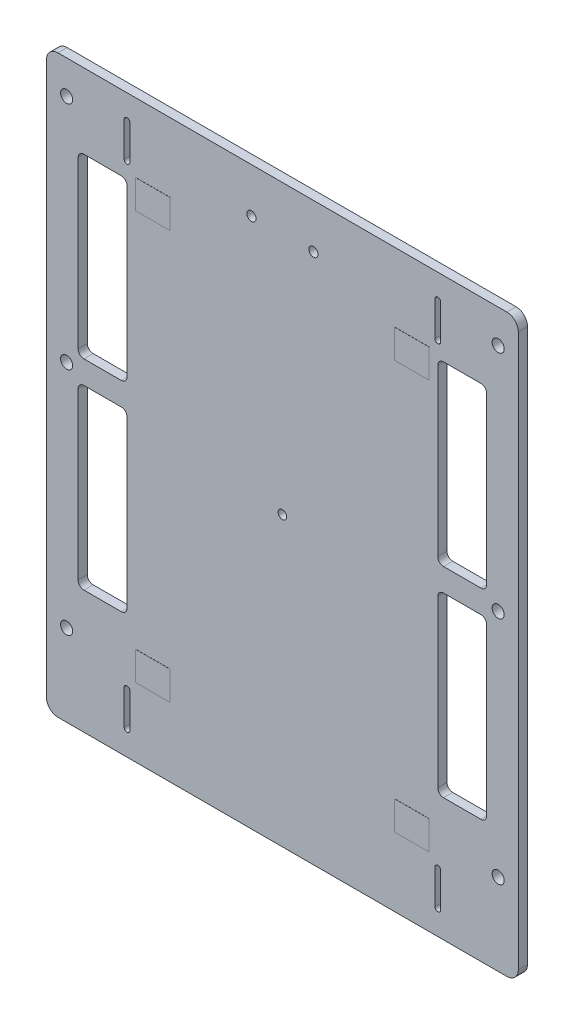
SolidWorks part; units mm, degrees
ref_plane "Front Plane" through (0, 0, 0) normal (0, 0, 1) x (1, 0, 0)
ref_plane "Top Plane" through (0, 0, 0) normal (0, 1, 0) x (1, 0, 0)
ref_plane "Right Plane" through (0, 0, 0) normal (1, 0, 0) x (0, 0, -1)
sketch "Sketch1" plane through (0, 0, 0) normal (0, 0, 1) x (1, 0, 0)
  line L1 (-39, -50) -> (39, -50)
  line L2 (-41, -48) -> (-41, 48)
  line L3 (-39, 50) -> (39, 50)
  line L4 (41, -48) -> (41, 48)
  line L5 (-41, -50) -> (41, 50) construction
  line L6 (-41, 50) -> (41, -50) construction
  arc A0 (-39, -50) -> (-41, -48) centre (-39, -48) cw
  arc A1 (39, -50) -> (41, -48) centre (39, -48) ccw
  arc A2 (39, 50) -> (41, 48) centre (39, 48) cw
  arc A3 (-41, 48) -> (-39, 50) centre (-39, 48) cw
  point P0 (0, 0)
  dimension "D3" = 2
  dimension "D1" = 100
  dimension "D2" = 82
extrude "Boss-Extrude1" add sketch "Sketch1" along normal blind 1.6
sketch "Sketch2" plane through (0, 0, 1.6) normal (0, 0, 1) x (1, 0, 0)
  line L0 (39, 50) -> (-39, 50) construction
  line L1 (-41, 48) -> (-41, -48) construction
  line L3 (-37.5, 44.2) -> (-37.5, 4.2) construction
  circle A0 centre (0, 0) radius 0.75
  circle A1 centre (-37.5, 44.2) radius 1.05
  circle A2 centre (37.5, 44.2) radius 1.05
  circle A3 centre (37.5, 4.2) radius 1.05
  circle A4 centre (37.5, -35.8) radius 1.05
  circle A5 centre (-37.5, 4.2) radius 1.05
  circle A6 centre (-37.5, -35.8) radius 1.05
  circle A7 centre (-5.38, 42.25) radius 0.8
  circle A8 centre (5.39, 42.25) radius 0.8
  dimension "D1" = 1.5
  dimension "D2" = 2.1
  dimension "D9" = 10.77
  dimension "D7" = 1.6
  dimension "D11" = 7.75
  dimension "D12" = 35.62
  dimension "D3" = 5.8
  dimension "D4" = 3.5
  dimension "D8" = 40
  dimension "D10" = 37.5
  dimension "D5" = 2
  dimension "D6" = 3
extrude "Cut-Extrude1" cut sketch "Sketch2" against normal through all
sketch "Sketch3" plane through (0, 0, 1.6) normal (0, 0, 1) x (1, 0, 0)
  line L0 (39, 50) -> (-39, 50) construction
  line L1 (-34.5, 37) -> (-28, 37)
  line L2 (-35.5, 36) -> (-35.5, 7.2)
  line L3 (-34.5, 6.2) -> (-28, 6.2)
  line L4 (-27, 36) -> (-27, 7.2)
  line L5 (-41, 48) -> (-41, -48) construction
  line L6 (28, 37) -> (34.5, 37)
  line L7 (27, 36) -> (27, 7.2)
  line L8 (35.5, 36) -> (35.5, 7.2)
  line L9 (28, 6.2) -> (34.5, 6.2)
  line L10 (28, 2.2) -> (34.5, 2.2)
  line L11 (27, 1.2) -> (27, -27.6)
  line L12 (35.5, 1.2) -> (35.5, -27.6)
  line L13 (28, -28.6) -> (34.5, -28.6)
  line L14 (-34.5, 2.2) -> (-28, 2.2)
  line L15 (-35.5, 1.2) -> (-35.5, -27.6)
  line L16 (-27, 1.2) -> (-27, -27.6)
  line L17 (-34.5, -28.6) -> (-28, -28.6)
  line L18 (-34.5, 37) -> (28, 37) construction
  line L19 (-39, -50) -> (39, -50) construction
  arc A0 (-35.5, 7.2) -> (-34.5, 6.2) centre (-34.5, 7.2) ccw
  arc A1 (-28, 6.2) -> (-27, 7.2) centre (-28, 7.2) ccw
  arc A2 (-28, 37) -> (-27, 36) centre (-28, 36) cw
  arc A3 (-34.5, 37) -> (-35.5, 36) centre (-34.5, 36) ccw
  arc A4 (28, 37) -> (27, 36) centre (28, 36) ccw
  arc A5 (34.5, 37) -> (35.5, 36) centre (34.5, 36) cw
  arc A6 (27, 7.2) -> (28, 6.2) centre (28, 7.2) ccw
  arc A7 (34.5, 6.2) -> (35.5, 7.2) centre (34.5, 7.2) ccw
  arc A8 (28, 2.2) -> (27, 1.2) centre (28, 1.2) ccw
  arc A9 (34.5, 2.2) -> (35.5, 1.2) centre (34.5, 1.2) cw
  arc A10 (27, -27.6) -> (28, -28.6) centre (28, -27.6) ccw
  arc A11 (34.5, -28.6) -> (35.5, -27.6) centre (34.5, -27.6) ccw
  arc A12 (-34.5, 2.2) -> (-35.5, 1.2) centre (-34.5, 1.2) ccw
  arc A13 (-28, 2.2) -> (-27, 1.2) centre (-28, 1.2) cw
  arc A14 (-35.5, -27.6) -> (-34.5, -28.6) centre (-34.5, -27.6) ccw
  arc A15 (-28, -28.6) -> (-27, -27.6) centre (-28, -27.6) ccw
  point P12 (-27, 6.2)
  point P15 (-27, 37)
  point P18 (-35.5, 37)
  dimension "D5" = 1
  dimension "D10" = 27
  dimension "D1" = 8.5
  dimension "D2" = 30.8
  dimension "D3" = 13
  dimension "D4" = 5.5
  dimension "D8" = 62.5
  dimension "D9" = 4
  dimension "D11" = 21.4
  dimension "D6" = 2
  dimension "D7" = 2
extrude "Cut-Extrude2" cut sketch "Sketch3" against normal through all
sketch "Sketch4" plane through (0, 0, 1.6) normal (0, 0, 1) x (1, 0, 0)
  line L0 (-27, 39.75) -> (-27, 45.75) construction
  line L1 (-27.5, 39.75) -> (-27.5, 45.75)
  line L2 (-26.5, 39.75) -> (-26.5, 45.75)
  line L3 (39, 50) -> (-39, 50) construction
  line L4 (-41, 48) -> (-41, -48) construction
  line L5 (27, 39.75) -> (27, 45.75) construction
  line L6 (26.5, 39.75) -> (26.5, 45.75)
  line L7 (27.5, 39.75) -> (27.5, 45.75)
  line L8 (27, -45.75) -> (27, -39.75) construction
  line L9 (26.5, -45.75) -> (26.5, -39.75)
  line L10 (27.5, -45.75) -> (27.5, -39.75)
  line L11 (-27, -45.75) -> (-27, -39.75) construction
  line L12 (-27.5, -45.75) -> (-27.5, -39.75)
  line L13 (-26.5, -45.75) -> (-26.5, -39.75)
  line L14 (-27, 39.75) -> (27, 39.75) construction
  line L15 (-39, -50) -> (39, -50) construction
  arc A0 (-27.5, 39.75) -> (-26.5, 39.75) centre (-27, 39.75) ccw
  arc A1 (-26.5, 45.75) -> (-27.5, 45.75) centre (-27, 45.75) ccw
  arc A2 (26.5, 39.75) -> (27.5, 39.75) centre (27, 39.75) ccw
  arc A3 (27.5, 45.75) -> (26.5, 45.75) centre (27, 45.75) ccw
  arc A4 (26.5, -45.75) -> (27.5, -45.75) centre (27, -45.75) ccw
  arc A5 (27.5, -39.75) -> (26.5, -39.75) centre (27, -39.75) ccw
  arc A6 (-27.5, -45.75) -> (-26.5, -45.75) centre (-27, -45.75) ccw
  arc A7 (-26.5, -39.75) -> (-27.5, -39.75) centre (-27, -39.75) ccw
  point P2 (-27, 42.75)
  point P16 (27, 42.75)
  point P23 (27, -42.75)
  point P30 (-27, -42.75)
  dimension "D1" = 4.25
  dimension "D2" = 13.5
  dimension "D3" = 1
  dimension "D4" = 6
  dimension "D7" = 54
  dimension "D8" = 14
  dimension "D9" = 4.25
  dimension "D10" = 4.25
  dimension "D5" = 2
  dimension "D6" = 2
extrude "Cut-Extrude3" cut sketch "Sketch4" against normal blind 1.6
sketch "Sketch5" plane through (0, 0, 1.6) normal (0, 0, 1) x (1, 0, 0)
  line L0 (-41, 48) -> (-41, -48) construction
  line L1 (-25.5, 38) -> (-19.5, 38)
  line L2 (-25.5, 38) -> (-25.5, 33)
  line L3 (-25.5, 33) -> (-19.5, 33)
  line L4 (-19.5, 38) -> (-19.5, 33)
  line L5 (39, 50) -> (-39, 50) construction
  line L6 (19.5, 38) -> (19.5, 33)
  line L7 (25.5, 38) -> (25.5, 33)
  line L8 (19.5, 33) -> (25.5, 33)
  line L9 (19.5, 38) -> (25.5, 38)
  line L10 (19.5, -33) -> (19.5, -38)
  line L11 (25.5, -33) -> (25.5, -38)
  line L12 (19.5, -38) -> (25.5, -38)
  line L13 (19.5, -33) -> (25.5, -33)
  line L14 (-25.5, -33) -> (-25.5, -38)
  line L15 (-19.5, -33) -> (-19.5, -38)
  line L16 (-25.5, -38) -> (-19.5, -38)
  line L17 (-25.5, -33) -> (-19.5, -33)
  line L18 (-25.5, 38) -> (19.5, 38) construction
  line L19 (-25.5, 38) -> (-25.5, -33) construction
  dimension "D1" = 5
  dimension "D2" = 6
  dimension "D3" = 15.5
  dimension "D4" = 12
  dimension "D7" = 45
  dimension "D8" = 71
  dimension "D5" = 2
  dimension "D6" = 2
extrude "Boss-Extrude2" add sketch "Sketch5" along normal blind 0.02
